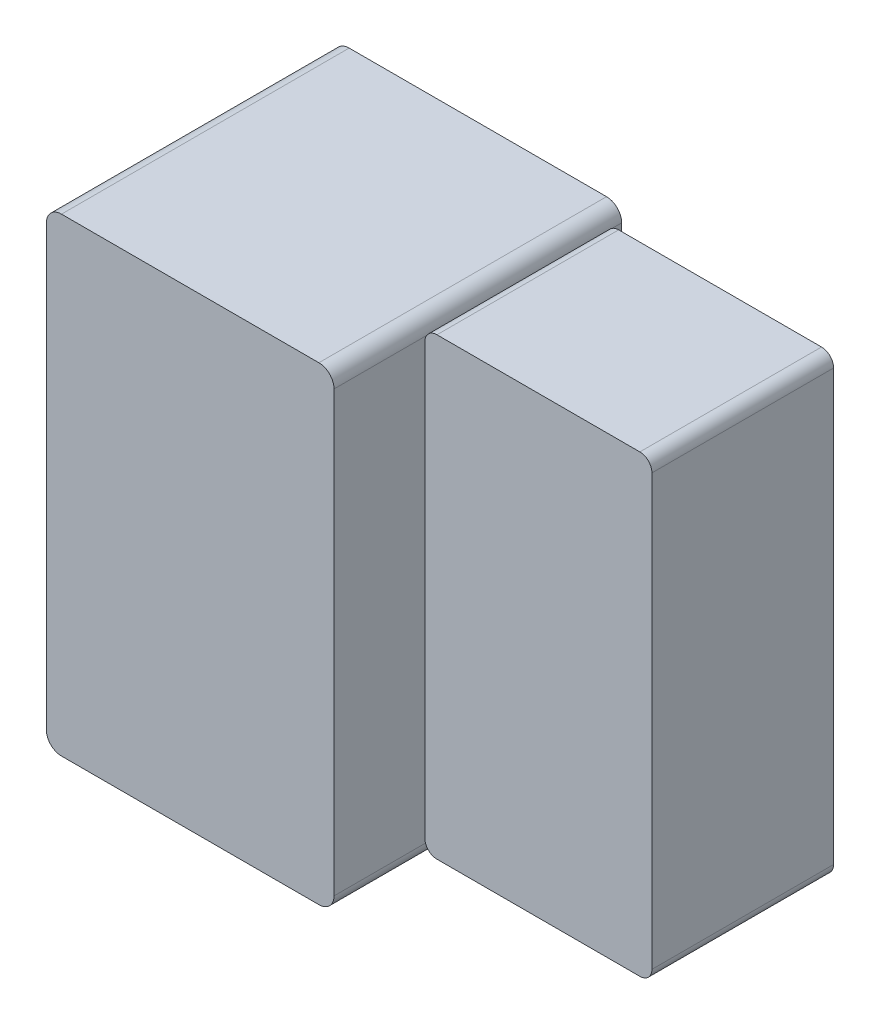
SolidWorks part; units mm, degrees
ref_plane "前视基准面" through (0, 0, 0) normal (0, 0, 1) x (1, 0, 0)
ref_plane "上视基准面" through (0, 0, 0) normal (0, 1, 0) x (1, 0, 0)
ref_plane "右视基准面" through (0, 0, 0) normal (1, 0, 0) x (0, 0, -1)
other "Configuration Table"
sketch "草图1" plane through (0, 0, 0) normal (0, 0, 1) x (1, 0, 0)
  line L0 (4.5, -7.75) -> (13, -7.75)
  line L1 (13.5, -7.25) -> (13.5, 7.25)
  line L2 (13, 7.75) -> (4.5, 7.75)
  line L3 (4, 7.25) -> (4, -7.25)
  arc A0 (4, -7.25) -> (4.5, -7.75) centre (4.5, -7.25) ccw
  arc A1 (13, -7.75) -> (13.5, -7.25) centre (13, -7.25) ccw
  arc A2 (13.5, 7.25) -> (13, 7.75) centre (13, 7.25) ccw
  arc A3 (4.5, 7.75) -> (4, 7.25) centre (4.5, 7.25) ccw
extrude "Header_budget_9p5x15p5_H9p5_plusX" add sketch "草图1" along normal blind 9.5
ref_plane "Plane_z_0.5_1" through (0, 0, 0.5) normal (0, 0, 1) x (1, 0, 0)
sketch "草图2" plane through (0, 0, 0.5) normal (0, 0, 1) x (1, 0, 0)
  line L0 (13.9, -7.5) -> (20.6, -7.5)
  line L1 (21, -7.1) -> (21, 7.1)
  line L2 (20.6, 7.5) -> (13.9, 7.5)
  line L3 (13.5, 7.1) -> (13.5, -7.1)
  arc A0 (13.5, -7.1) -> (13.9, -7.5) centre (13.9, -7.1) ccw
  arc A1 (20.6, -7.5) -> (21, -7.1) centre (20.6, -7.1) ccw
  arc A2 (21, 7.1) -> (20.6, 7.5) centre (20.6, 7.1) ccw
  arc A3 (13.9, 7.5) -> (13.5, 7.1) centre (13.9, 7.1) ccw
extrude "Mated_plug_budget_outward_plusX" add sketch "草图2" along normal blind 6
